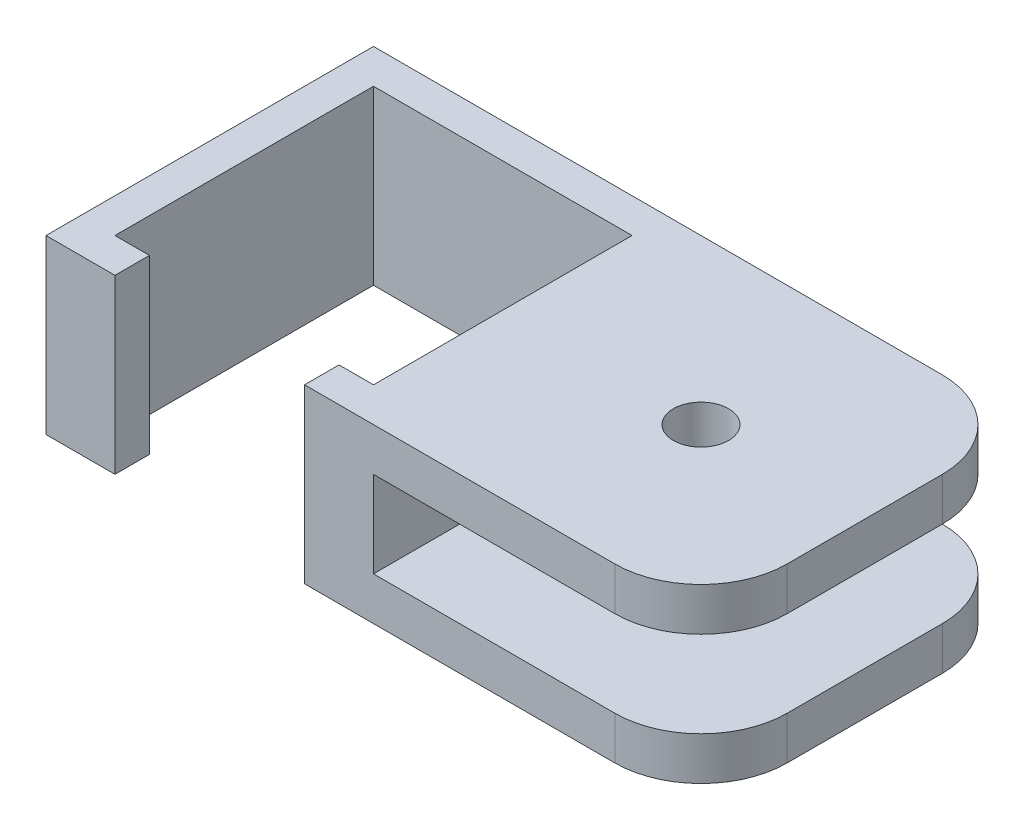
SolidWorks part; units mm, degrees
ref_plane "前视基准面" through (0, 0, 0) normal (0, 0, 1) x (1, 0, 0)
ref_plane "上视基准面" through (0, 0, 0) normal (0, 1, 0) x (1, 0, 0)
ref_plane "右视基准面" through (0, 0, 0) normal (1, 0, 0) x (0, 0, -1)
sketch "草图1" plane through (0, 0, 0) normal (0, 1, 0) x (1, 0, 0)
  line L0 (-7.4044, -8.6728) -> (-5.4044, -8.6728)
  line L1 (-7.4044, 6.3272) -> (7.5956, 6.3272)
  line L2 (-7.4044, 6.3272) -> (-7.4044, -8.6728)
  line L4 (7.5956, 6.3272) -> (7.5956, -8.6728)
  line L5 (-5.4044, -8.6728) -> (-5.4044, -10.6728)
  line L6 (-5.4044, -10.6728) -> (-9.4044, -10.6728)
  line L7 (-9.4044, -10.6728) -> (-9.4044, 8.3272)
  line L8 (-9.4044, 8.3272) -> (9.5956, 8.3272)
  line L9 (9.5956, 8.3272) -> (9.5956, -10.6728)
  line L10 (9.5956, -10.6728) -> (5.5956, -10.6728)
  line L11 (5.5956, -10.6728) -> (5.5956, -8.6728)
  line L12 (5.5956, -8.6728) -> (7.5956, -8.6728)
  point P8 (-7.4044, -10.6728)
  dimension "D1" = 15
  dimension "D2" = 15
  dimension "D3" = 15
  dimension "D4" = 2
  dimension "D5" = 2
  dimension "D6" = 2
  dimension "D7" = 2
  dimension "D8" = 2
  dimension "D9" = 2
  dimension "D10" = 2
extrude "凸台-拉伸3" add sketch "草图1" along normal blind 10
sketch "草图5" plane through (9.5956, 0, 0) normal (1, 0, 0) x (0, 0, -1)
  line L0 (8.3272, 10) -> (8.3272, 0) construction
  line L1 (-10.6728, 10) -> (8.3272, 10)
  line L2 (-10.6728, 10) -> (-10.6728, 7)
  line L3 (-10.6728, 7) -> (8.3272, 7)
  line L4 (8.3272, 10) -> (8.3272, 7)
  line L6 (-10.6728, 0) -> (8.3272, 0)
  line L7 (-10.6728, 0) -> (-10.6728, 3)
  line L8 (-10.6728, 3) -> (8.3272, 3)
  line L9 (8.3272, 0) -> (8.3272, 3)
  dimension "D1" = 3
  dimension "D2" = 3
  dimension "D3" = 19
extrude "凸台-拉伸5" add sketch "草图5" along normal blind 19
sketch "草图6" plane through (0, 0, 0) normal (0, -1, 0) x (1, 0, 0)
  line L0 (5.5956, 10.6728) -> (28.5956, 10.6728) construction
  line L1 (23.5956, -8.3272) -> (9.5956, -8.3272) construction
  line L2 (28.5956, -3.3272) -> (28.5956, 5.6728) construction
  line L3 (23.5956, 10.6728) -> (9.5956, 10.6728) construction
  line L4 (9.5956, -8.3272) -> (9.5956, 10.6728) construction
  line L5 (23.5956, 10.6728) -> (28.5956, 10.6728)
  line L6 (28.5956, 10.6728) -> (28.5956, 5.6728)
  line L7 (28.5956, -3.3272) -> (28.5956, -8.3272)
  line L8 (28.5956, -8.3272) -> (23.5956, -8.3272)
  circle A0 centre (19.0956, 1.1728) radius 1.6
  arc A1 (23.5956, 10.6728) -> (28.5956, 5.6728) centre (23.5956, 5.6728) cw
  arc A2 (28.5956, -3.3272) -> (23.5956, -8.3272) centre (23.5956, -3.3272) cw
  point P7 (9.5956, 1.1728)
  point P8 (16.5956, 10.6728)
  point P15 (28.5956, -8.3272)
  dimension "D2" = 9.5
  dimension "D4" = 5
  dimension "D1" = 19
  dimension "D3" = 9.5
extrude "切除-拉伸4" cut sketch "草图6" against normal blind 19
sketch "草图7" plane through (0, 7, 0) normal (0, -1, 0) x (1, 0, 0)
  line L0 (23.5956, -8.3272) -> (9.5956, -8.3272) construction
  line L1 (9.5956, 10.6728) -> (28.5956, 10.6728)
  line L2 (9.5956, 10.6728) -> (9.5956, -8.3272)
  line L3 (9.5956, -8.3272) -> (28.5956, -8.3272)
  line L4 (28.5956, 10.6728) -> (28.5956, -8.3272)
  line L5 (9.5956, 10.6728) -> (28.5956, -8.3272) construction
  line L6 (9.5956, -8.3272) -> (28.5956, 10.6728) construction
  point P4 (19.0956, 1.1728)
extrude "切除-拉伸5" cut sketch "草图7" against normal blind 0.5
sketch "草图8" plane through (0, 3, 0) normal (0, 1, 0) x (1, 0, 0)
  line L0 (28.5956, 3.3272) -> (28.5956, -5.6728) construction
  line L1 (9.5956, 8.3272) -> (28.5956, 8.3272)
  line L2 (9.5956, 8.3272) -> (9.5956, -10.6728)
  line L3 (9.5956, -10.6728) -> (28.5956, -10.6728)
  line L4 (28.5956, 8.3272) -> (28.5956, -10.6728)
  line L5 (9.5956, 8.3272) -> (28.5956, -10.6728) construction
  line L6 (9.5956, -10.6728) -> (28.5956, 8.3272) construction
  line L7 (23.5956, -10.6728) -> (9.5956, -10.6728) construction
  point P4 (19.0956, -1.1728)
extrude "切除-拉伸7" cut sketch "草图8" against normal blind 0.5
